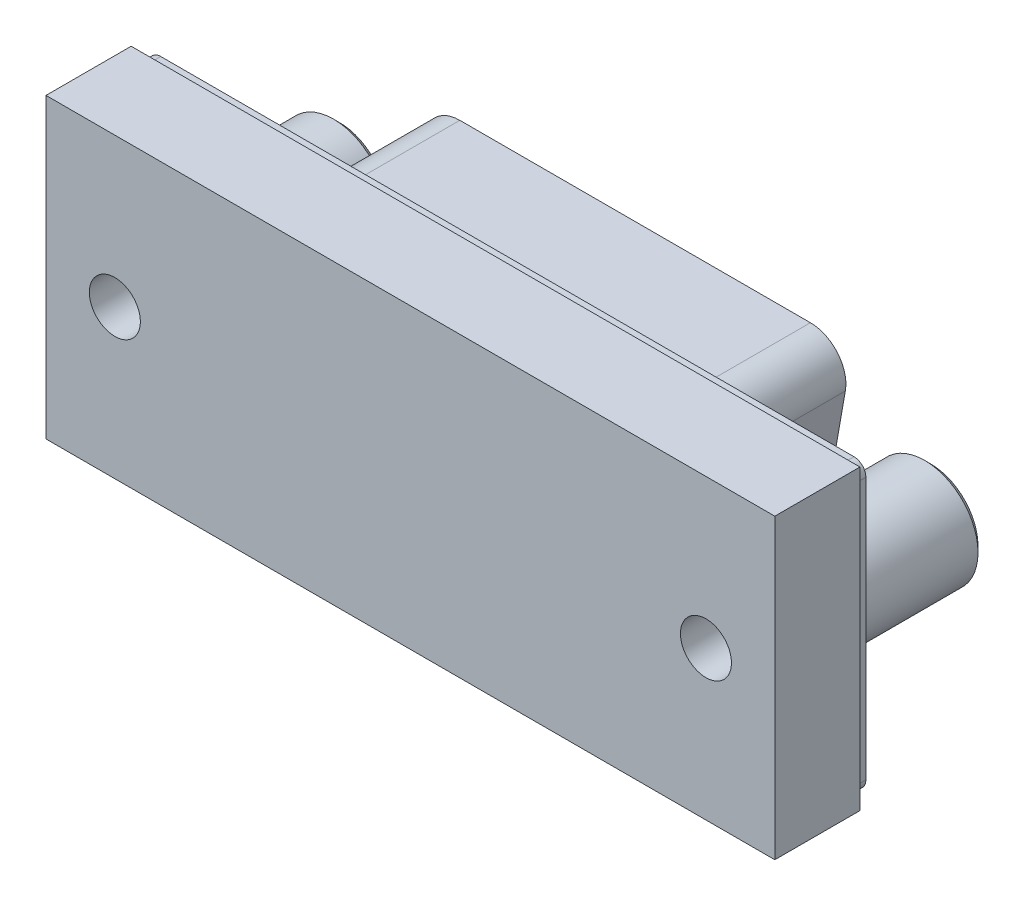
SolidWorks part; units mm, degrees
ref_plane "Front Plane" through (0, 0, 0) normal (0, 0, 1) x (1, 0, 0)
ref_plane "Top Plane" through (0, 0, 0) normal (0, 1, 0) x (1, 0, 0)
ref_plane "Right Plane" through (0, 0, 0) normal (1, 0, 0) x (0, 0, -1)
ref_plane "Plane1" through (-15.405, 0, 0) normal (-1, 0, 0) x (0, -1, 0)
sketch "Sketch1" plane through (-15.405, 0, 0) normal (-1, 0, 0) x (0, -1, 0)
  line L0 (-12.58, -3.6) -> (0, -3.6)
  line L1 (0, -3.6) -> (0, 0)
  line L2 (0, 0) -> (-3.6, 0)
  line L3 (-3.6, 0) -> (-12.58, 0)
  line L4 (-12.58, 0) -> (-12.58, -3.6)
extrude "Boss-Extrude1" add sketch "Sketch1" against normal blind 30.81
ref_plane "Plane2" through (0, 0, -4.1) normal (0, 0, -1) x (-1, 0, 0)
sketch "Sketch2" plane through (0, 0, -4.1) normal (0, 0, -1) x (-1, 0, 0)
  line L0 (-15.155, 11.83) -> (-15.155, 0.75)
  line L1 (-14.655, 0.25) -> (14.655, 0.25)
  line L2 (15.155, 0.75) -> (15.155, 11.83)
  line L3 (14.655, 12.33) -> (-14.655, 12.33)
  arc A0 (-14.655, 12.33) -> (-15.155, 11.83) centre (-14.655, 11.83) ccw
  arc A1 (-15.155, 0.75) -> (-14.655, 0.25) centre (-14.655, 0.75) ccw
  arc A2 (14.655, 0.25) -> (15.155, 0.75) centre (14.655, 0.75) ccw
  arc A3 (15.155, 11.83) -> (14.655, 12.33) centre (14.655, 11.83) ccw
extrude "Boss-Extrude2" add sketch "Sketch2" against normal up to surface (0.5 mm away) up to face at (0, 6.29, -3.6)
ref_plane "Plane3" through (0, 0, -9.5) normal (0, 0, -1) x (-1, 0, 0)
sketch "Sketch3" plane through (0, 0, -9.5) normal (0, 0, -1) x (-1, 0, 0)
  line L0 (-8.8874, 9.1545) -> (-7.7854, 2.9045)
  line L1 (-6.3081, 1.665) -> (6.3081, 1.665)
  line L2 (7.7854, 2.9045) -> (8.8874, 9.1545)
  line L3 (7.4102, 10.915) -> (-7.4102, 10.915)
  arc A0 (-7.4102, 10.915) -> (-8.8874, 9.1545) centre (-7.4102, 9.415) ccw
  arc A1 (-7.7854, 2.9045) -> (-6.3081, 1.665) centre (-6.3081, 3.165) ccw
  arc A2 (6.3081, 1.665) -> (7.7854, 2.9045) centre (6.3081, 3.165) ccw
  arc A3 (8.8874, 9.1545) -> (7.4102, 10.915) centre (7.4102, 9.415) ccw
extrude "Boss-Extrude3" add sketch "Sketch3" against normal up to surface (5.4 mm away) up to face at (0, 6.29, -4.1)
ref_plane "Plane4" through (0, 0, -3.6) normal (0, 0, 1) x (1, 0, 0)
sketch "Sketch4" plane through (0, 0, -3.6) normal (0, 0, 1) x (1, 0, 0)
  line L0 (7.4102, 10.415) -> (-7.4102, 10.415)
  line L1 (-8.395, 9.2414) -> (-7.293, 2.9914)
  line L2 (-6.3081, 2.165) -> (6.3081, 2.165)
  line L3 (7.293, 2.9914) -> (8.395, 9.2414)
  arc A0 (8.395, 9.2414) -> (7.4102, 10.415) centre (7.4102, 9.415) ccw
  arc A1 (-7.4102, 10.415) -> (-8.395, 9.2414) centre (-7.4102, 9.415) ccw
  arc A2 (-7.293, 2.9914) -> (-6.3081, 2.165) centre (-6.3081, 3.165) ccw
  arc A3 (6.3081, 2.165) -> (7.293, 2.9914) centre (6.3081, 3.165) ccw
extrude "Cut-Extrude1" cut sketch "Sketch4" against normal up to next
sketch "Sketch15" plane through (0, 0, -9.5) normal (0, 0, -1) x (-1, 0, 0)
  circle A0 centre (-12.495, 6.29) radius 2.25
  circle A1 centre (12.495, 6.29) radius 2.25
extrude "Boss-Extrude14" add sketch "Sketch15" against normal up to next
hole_wizard "Hole1" positions "Sketch17" profile "Sketch16" legacy
sketch "Sketch17" plane through (0, 0, -9.5) normal (0, 0, -1) x (-1, 0, 0)
  point P0 (12.495, 6.29)
  point P1 (-12.495, 6.29)
sketch "Sketch16" plane through (-12.495, 6.29, -9.5) normal (1, 0, 0) x (0, 1, 0)
  line L0 (0, 0) -> (0, 9.5)
  line L1 (0, 9.5) -> (1.078, 9.5)
  line L2 (1.078, 9.5) -> (1.078, 0)
  line L3 (1.078, 0) -> (0, 0)
  line L4 (0, 110) -> (0, -10) construction
  dimension "Diameter" = 2.156
  dimension "Depth" = 9.5
chamfer "Chamfer1" distance 0.25 angle 45 4 edges at (-10.245, 6.29, -9.5) (14.745, 6.29, -9.5) (11.417, 6.29, -9.5) (-13.573, 6.29, -9.5)
sketch "Sketch19" plane through (0, 0, -3.6) normal (0, 0, -1) x (-1, 0, 0)
  circle A9 centre (-5.48, 7.71) radius 0.335
  circle A10 centre (-2.74, 7.71) radius 0.335
  circle A11 centre (0, 7.71) radius 0.335
  circle A12 centre (2.74, 7.71) radius 0.335
  circle A13 centre (5.48, 7.71) radius 0.335
  circle A14 centre (4.11, 4.87) radius 0.335
  circle A15 centre (1.37, 4.87) radius 0.335
  circle A16 centre (-1.37, 4.87) radius 0.335
  circle A17 centre (-4.11, 4.87) radius 0.335
extrude "Boss-Extrude15" add sketch "Sketch19" along normal blind 4.9962
